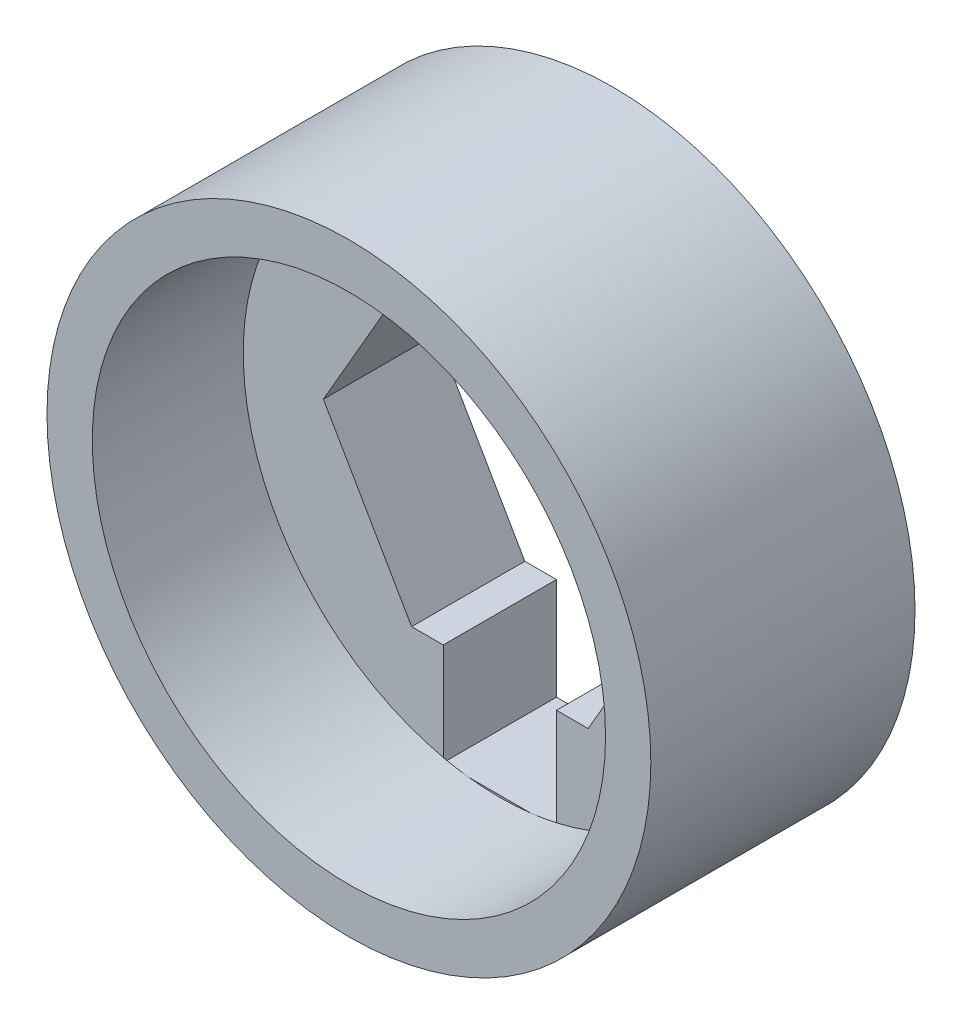
SolidWorks part; units mm, degrees
ref_plane "Front Plane" through (0, 0, 0) normal (0, 0, 1) x (1, 0, 0)
ref_plane "Top Plane" through (0, 0, 0) normal (0, 1, 0) x (1, 0, 0)
ref_plane "Right Plane" through (0, 0, 0) normal (1, 0, 0) x (0, 0, -1)
sketch "Sketch1" plane through (0, 0, 0) normal (0, 0, 1) x (1, 0, 0)
  circle A0 centre (0, 0) radius 8
  dimension "D1" = 16
extrude "Boss-Extrude1" add sketch "Sketch1" along normal blind 7
sketch "Sketch2" plane through (0, 0, 7) normal (0, 0, 1) x (1, 0, 0)
  circle A0 centre (0, 0) radius 6.8
  circle A1 centre (0, 0) radius 8 construction
  dimension "D1" = 1.2
extrude "Cut-Extrude1" cut sketch "Sketch2" against normal blind 4
sketch "Sketch3" plane through (0, 0, 0) normal (0, 0, 1) x (1, 0, 0)
  line L1 (4.6765, 0) -> (2.3383, 4.05)
  line L2 (2.3383, 4.05) -> (-2.3383, 4.05)
  line L3 (-2.3383, 4.05) -> (-4.6765, 0)
  line L4 (-4.6765, 0) -> (-2.3383, -4.05)
  line L5 (-2.3383, -4.05) -> (2.3383, -4.05)
  line L6 (2.3383, -4.05) -> (4.6765, 0)
  circle A0 centre (0, 0) radius 4.05 construction
  dimension "D1" = 8.1
extrude "Cut-Extrude2" cut sketch "Sketch3" along normal blind 4
sketch "Sketch5" plane through (0, 0, 3) normal (0, 0, 1) x (1, 0, 0)
  line L0 (-2.3383, 4.05) -> (2.3383, 4.05) construction
  line L1 (-1.5, 6.75) -> (1.5, 6.75)
  line L2 (-1.5, 6.75) -> (-1.5, 3.75)
  line L3 (-1.5, 3.75) -> (1.5, 3.75)
  line L4 (1.5, 6.75) -> (1.5, 3.75)
  line L5 (-1.5, -3.75) -> (1.5, -3.75)
  line L6 (-1.5, -3.75) -> (-1.5, -6.75)
  line L7 (-1.5, -6.75) -> (1.5, -6.75)
  line L8 (1.5, -3.75) -> (1.5, -6.75)
  line L9 (2.3383, -4.05) -> (-2.3383, -4.05) construction
  point P9 (0, 3.75)
  point P14 (0, -6.75)
  dimension "D1" = 1.5
  dimension "D2" = 1.5
  dimension "D3" = 3
  dimension "D4" = 2.7
  dimension "D5" = 2.7
  dimension "D6" = 3
extrude "Cut-Extrude4" cut sketch "Sketch5" against normal through all
